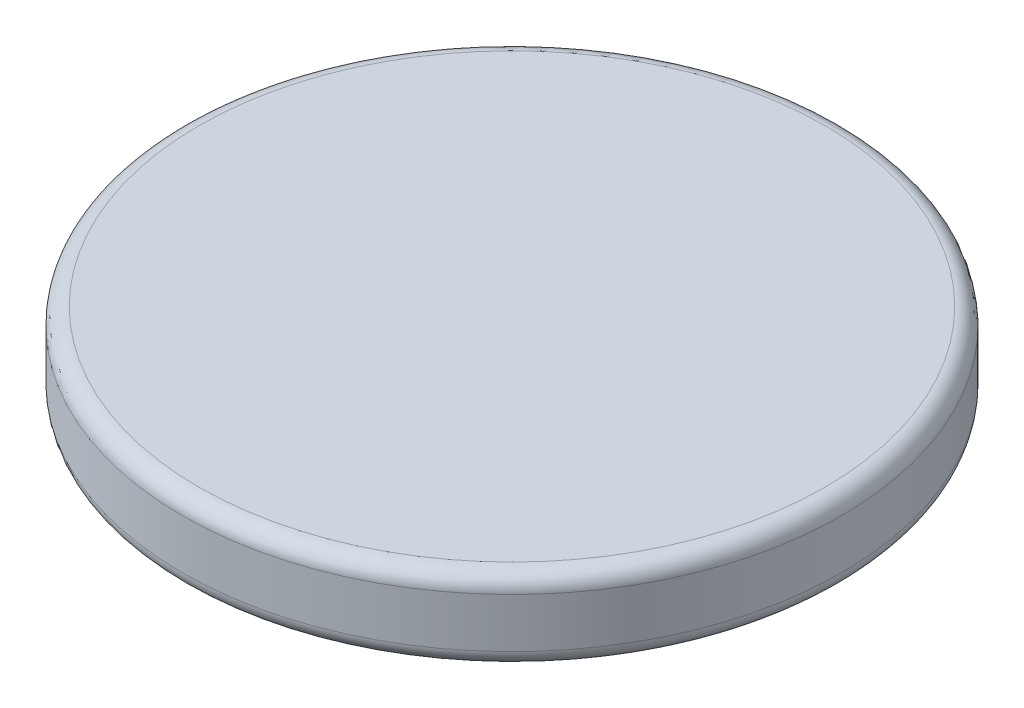
SolidWorks part; units mm, degrees
ref_plane "Front Plane" through (0, 0, 0) normal (0, 0, 1) x (1, 0, 0)
ref_plane "Top Plane" through (0, 0, 0) normal (0, 1, 0) x (1, 0, 0)
ref_plane "Right Plane" through (0, 0, 0) normal (1, 0, 0) x (0, 0, -1)
sketch "Sketch4" plane through (0, 0, 0) normal (0, 1, 0) x (1, 0, 0)
  circle A0 centre (0, 0) radius 40
  dimension "D1" = 80
extrude "Boss-Extrude1" add sketch "Sketch4" along normal blind 10
fillet "Fillet1" radius 2 2 edges at (0, 10, 40) (0, 0, 40)
